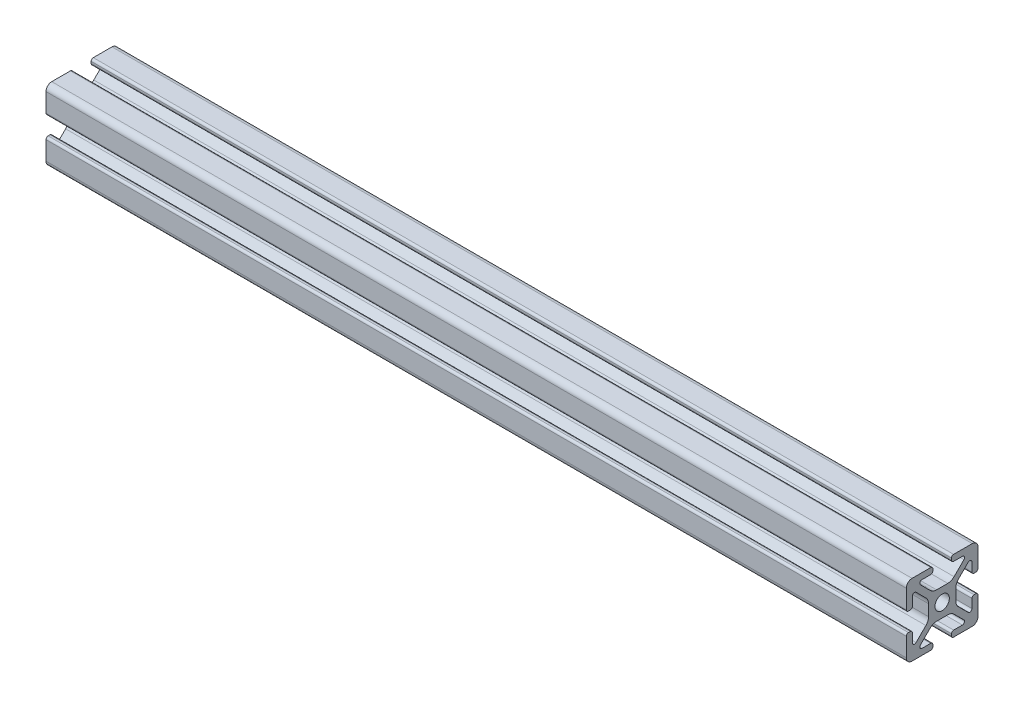
SolidWorks part; units mm, degrees
ref_plane "Front Plane" through (0, 0, 0) normal (0, 0, 1) x (1, 0, 0)
ref_plane "Top Plane" through (0, 0, 0) normal (0, 1, 0) x (1, 0, 0)
ref_plane "Right Plane" through (0, 0, 0) normal (1, 0, 0) x (0, 0, -1)
sketch "Sketch1" plane through (0, 0, 0) normal (1, 0, 0) x (0, 0, -1)
  line L0 (0, -12.7) -> (0, 12.7) construction
  line L1 (-7.874, 12.7) -> (7.874, 12.7) construction
  line L2 (-12.7, 0) -> (12.7, 0) construction
  line L3 (-7.874, 12.7) -> (-7.874, 4.826) construction
  line L4 (-3.302, 12.7) -> (3.302, 12.7) construction
  line L5 (-12.7, -12.7) -> (12.7, -12.7) construction
  line L6 (-12.7, 12.7) -> (12.7, 12.7) construction
  circle A0 centre (0, 0) radius 2.54 construction
  point P7 (0, 12.7)
  point P10 (0, 0)
  point P13 (0, 0)
  point P16 (0, 12.7)
  point P17 (-3.302, 12.7)
  point P18 (3.302, 12.7)
  point P21 (0, -12.7)
  point P24 (0, 12.7)
  dimension "Center Hole Diameter" = 5.08
  dimension "Rail Width" = 25.4
  dimension "Rail Height" = 25.4
  dimension "T-Slot Depth" = 7.874
  dimension "D1" = 15.748
  dimension "T-Slot Width" = 6.604
  dimension "D2" = 12.7
sketch "Sketch2" plane through (0, 0, 0) normal (0, 0, 1) x (1, 0, 0)
  line L0 (-152.4, 0) -> (152.4, 0) construction
  line L1 (0, 0) -> (0, 26.104) construction
  line L2 (152.4, -12.7) -> (152.4, 12.7) construction
  line L3 (-152.4, -12.7) -> (-152.4, 12.7) construction
  point P3 (-114.3, 0)
  point P8 (0, 0)
  point P9 (114.3, 0)
  point P12 (152.4, 0)
  point P15 (-152.4, 0)
  dimension "Length" = 304.8
  dimension "D1" = 38.1
  dimension "D2" = 25.4
sketch "Sketch3" plane through (0, 0, 0) normal (1, 0, 0) x (0, 0, -1)
  line L0 (0, 4.826) -> (1.9842, 4.826)
  line L1 (0, -12.7) -> (0, 12.7) construction
  line L2 (4.2293, 5.7559) -> (7.7135, 9.2402)
  line L6 (7.1747, 10.541) -> (4.064, 10.541)
  line L7 (3.302, 11.303) -> (3.302, 11.938)
  line L8 (-7.874, 12.7) -> (7.874, 12.7) construction
  line L10 (0, 0) -> (12.7, 12.7) construction
  line L13 (0, 4.826) -> (0, 2.54)
  line L14 (4.826, 0) -> (2.54, 0)
  line L31 (4.826, 0) -> (4.826, 1.9842)
  line L32 (4.064, 12.7) -> (10.668, 12.7)
  line L33 (-12.7, 0) -> (12.7, 0) construction
  line L34 (-12.7, 12.7) -> (12.7, 12.7) construction
  line L35 (5.7559, 4.2293) -> (9.2402, 7.7135)
  line L36 (0, 12.7) -> (12.7, 12.7) construction
  line L37 (12.7, 12.7) -> (12.7, 8.0234) construction
  line L38 (11.303, 3.302) -> (11.938, 3.302)
  line L39 (10.541, 7.1747) -> (10.541, 4.064)
  line L40 (12.7, 10.668) -> (12.7, 4.064)
  arc A0 (2.54, 0) -> (0, 2.54) centre (0, 0) ccw
  arc A1 (1.9842, 4.826) -> (4.2293, 5.7559) centre (1.9842, 8.001) ccw
  circle A2 centre (0, 0) radius 2.54 construction
  arc A7 (3.302, 11.938) -> (4.064, 12.7) centre (4.064, 11.938) cw
  arc A8 (4.064, 10.541) -> (3.302, 11.303) centre (4.064, 11.303) cw
  arc A14 (4.826, 1.9842) -> (5.7559, 4.2293) centre (8.001, 1.9842) cw
  arc A16 (10.668, 12.7) -> (12.7, 10.668) centre (10.668, 10.668) cw
  arc A17 (7.1747, 10.541) -> (7.7135, 9.2402) centre (7.1747, 9.779) cw
  arc A18 (10.541, 7.1747) -> (9.2402, 7.7135) centre (9.779, 7.1747) ccw
  arc A19 (10.541, 4.064) -> (11.303, 3.302) centre (11.303, 4.064) ccw
  arc A20 (11.938, 3.302) -> (12.7, 4.064) centre (11.938, 4.064) ccw
  point P37 (3.2994, 4.826)
  point P49 (12.7, 3.302)
  point P52 (3.302, 12.7)
  point P55 (3.302, 10.541)
  dimension "D4" = 3.175
  dimension "D9" = 2.159
  dimension "D12" = 0.762
  dimension "D3" = 2.032
  dimension "D8" = 0.762
  dimension "D2" = 45
  dimension "D5" = 0
  dimension "D6" = 45
  dimension "D7" = 2.159
extrude "Boss-Extrude1" add sketch "Sketch3" against normal up to vertex (152.4 mm away) and the other way up to vertex (152.4 mm away) up to point (-152.4, 0, 0) other way up to point (152.4, 0, 0)
mirror "Mirror1" about plane through (0, 0, 0) normal (0, 1, 0) of bodies 104
mirror "Mirror2" about plane through (0, 0, 0) normal (0, 0, 1) of bodies 105
equation "\"D1@Sketch2\"=\"Rail Height@Sketch1\"*1.5"
equation "\"D2@Sketch2\"=\"Rail Height@Sketch1\""
